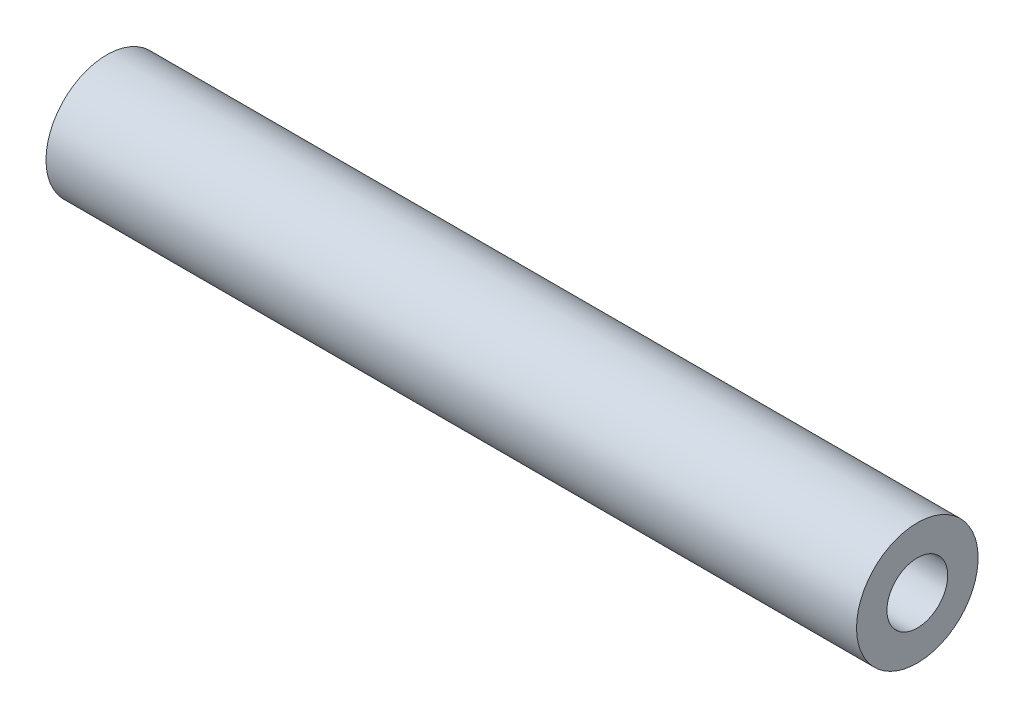
SolidWorks part; units mm, degrees
ref_plane "Front Plane" through (0, 0, 0) normal (0, 0, 1) x (1, 0, 0)
ref_plane "Top Plane" through (0, 0, 0) normal (0, 1, 0) x (1, 0, 0)
ref_plane "Right Plane" through (0, 0, 0) normal (1, 0, 0) x (0, 0, -1)
sketch "Sketch1" plane through (0, 0, 0) normal (0, 0, 1) x (1, 0, 0)
  line L0 (0, 0) -> (240, 0) construction
  line L1 (20, 7.5) -> (220, 7.5)
  line L6 (20, 15) -> (220, 15)
  line L7 (20, 15) -> (20, 7.5)
  line L9 (220, 15) -> (220, 7.5)
  dimension "L" = 240
  dimension "D_s" = 15
  dimension "D" = 30
revolve "Revolve1" add sketch "Sketch1" angle 360 about L0
